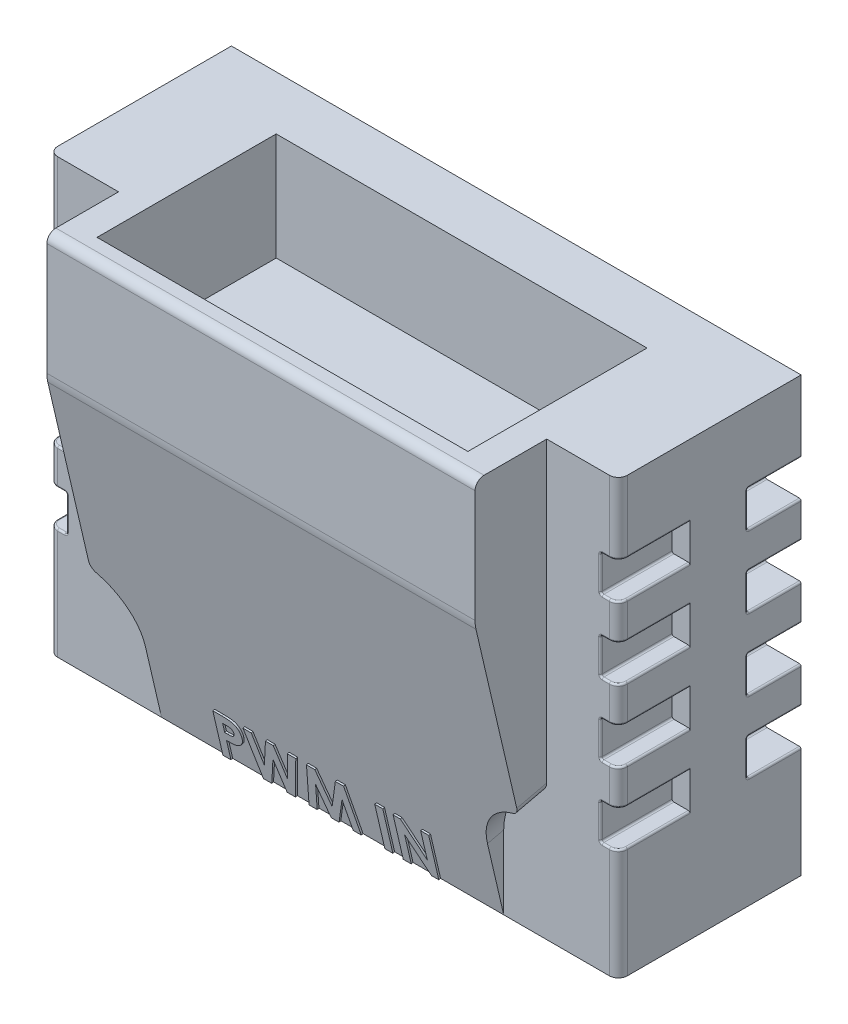
SolidWorks part; units mm, degrees
material "Polyester Resin"
ref_plane "Front Plane" through (0, 0, 0) normal (0, 0, 1) x (1, 0, 0)
ref_plane "Top Plane" through (0, 0, 0) normal (0, 1, 0) x (1, 0, 0)
ref_plane "Right Plane" through (0, 0, 0) normal (1, 0, 0) x (0, 0, -1)
sketch "Sketch1" plane through (0, 0, 0) normal (0, 0, 1) x (1, 0, 0)
  line L1 (-15.9, 12.1) -> (15.9, 12.1)
  line L2 (-15.9, 12.1) -> (-15.9, -12.1)
  line L3 (-15.9, -12.1) -> (15.9, -12.1)
  line L4 (15.9, 12.1) -> (15.9, -12.1)
  point P6 (0, 12.1)
  point P7 (15.9, 0)
  dimension "D1" = 31.8
  dimension "D2" = 24.2
extrude "Boss-Extrude1" add sketch "Sketch1" along normal mid plane 10.2
sketch "Sketch3" plane through (15.9, 0, 0) normal (1, 0, 0) x (0, 0, -1)
  line L0 (-5.1, -12.1) -> (-5.7982, -9.0978)
  line L1 (-5.7982, -9.0978) -> (-9.1, 5.1)
  line L2 (-9.1, 5.1) -> (-9.1, 12.1)
  line L3 (-9.1, 12.1) -> (-5.1, 12.1)
  line L4 (-5.1, 12.1) -> (-5.1, -12.1)
  line L5 (-5.1, 12.1) -> (5.1, 12.1) construction
  dimension "D1" = 4
  dimension "D2" = 7
extrude "Boss-Extrude2" add sketch "Sketch3" against normal blind 23.9 from offset 4 offset against normal yes
fillet "Fillet1" radius 2 1 edges at (-0.05, 5.1, 9.1)
fillet "Fillet2" radius 0.5 1 edges at (-0.05, 12.1, 9.1)
sketch "Sketch4" plane through (0, -1.746, 7.5079) normal (0, -0.2265, 0.974) x (1, 0, 0)
  line L0 (11.9, 6.7992) -> (11.9, -10.6303) construction
  line L1 (-12, 6.7992) -> (-12, -10.6303) construction
  line L2 (-9.6, -6.6303) -> (-9.6, -10.6303)
  line L3 (-12, -10.6303) -> (11.9, -10.6303) construction
  line L4 (-9.6, -10.6303) -> (-12, -10.6303)
  line L5 (-12, -10.6303) -> (-12, -3.6303)
  line L6 (9.5, -6.6303) -> (9.5, -10.6303)
  line L7 (9.5, -10.6303) -> (11.9, -10.6303)
  line L8 (11.9, -10.6303) -> (11.9, -3.6303)
  arc A0 (11.9, -3.6303) -> (9.5, -6.6303) centre (12.575, -6.6303) ccw
  arc A1 (-12, -3.6303) -> (-9.6, -6.6303) centre (-12.675, -6.6303) cw
  dimension "D1" = 2.4
  dimension "D2" = 3
  dimension "D3" = 7
extrude "Cut-Extrude1" cut sketch "Sketch4" against normal up to surface up to face at (-13.95, 0, 5.1)
fillet "Fillet4" radius 0.5 2 edges at (11.9, -5.0976, 5.8928) (-12, -5.0976, 5.8928)
sketch "Sketch5" plane through (0, 0, 5.1) normal (0, 0, 1) x (1, 0, 0)
  line L0 (15.9, -12.1) -> (15.9, 12.1) construction
  line L1 (9.5, -12.1) -> (15.9, -12.1) construction
  line L2 (0, 0) -> (0, 13.9724) construction
  line L3 (15.9, 12.1) -> (11.9, 12.1) construction
  line L4 (15.9, 8.1) -> (14.9, 8.1)
  line L5 (15.9, 8.1) -> (15.9, 6.1)
  line L6 (15.9, 6.1) -> (14.9, 6.1)
  line L7 (14.9, 8.1) -> (14.9, 6.1)
  line L8 (15.9, 4.1) -> (14.9, 4.1)
  line L9 (15.9, 4.1) -> (15.9, 2.1)
  line L10 (15.9, 2.1) -> (14.9, 2.1)
  line L11 (14.9, 4.1) -> (14.9, 2.1)
  line L12 (-15.9, -5.9) -> (-14.9, -5.9)
  line L13 (15.9, 0.1) -> (14.9, 0.1)
  line L14 (15.9, 0.1) -> (15.9, -1.9)
  line L15 (15.9, -1.9) -> (14.9, -1.9)
  line L16 (14.9, 0.1) -> (14.9, -1.9)
  line L17 (15.9, -3.9) -> (14.9, -3.9)
  line L18 (15.9, -3.9) -> (15.9, -5.9)
  line L19 (15.9, -5.9) -> (14.9, -5.9)
  line L20 (14.9, -3.9) -> (14.9, -5.9)
  line L21 (-14.9, -3.9) -> (-14.9, -5.9)
  line L22 (-15.9, -3.9) -> (-14.9, -3.9)
  line L23 (-15.9, -3.9) -> (-15.9, -5.9)
  line L24 (-15.9, -1.9) -> (-14.9, -1.9)
  line L25 (-14.9, 0.1) -> (-14.9, -1.9)
  line L26 (-15.9, 0.1) -> (-14.9, 0.1)
  line L27 (-15.9, 0.1) -> (-15.9, -1.9)
  line L28 (-15.9, 4.1) -> (-15.9, 2.1)
  line L29 (-15.9, 8.1) -> (-15.9, 6.1)
  line L30 (-15.9, 2.1) -> (-14.9, 2.1)
  line L31 (-14.9, 4.1) -> (-14.9, 2.1)
  line L32 (-15.9, 4.1) -> (-14.9, 4.1)
  line L33 (-15.9, 6.1) -> (-14.9, 6.1)
  line L34 (-14.9, 8.1) -> (-14.9, 6.1)
  line L35 (-15.9, 8.1) -> (-14.9, 8.1)
  circle A0 centre (13.4, -9.6) radius 1.6
  circle A1 centre (-13.4, -9.6) radius 1.6
  dimension "D1" = 2.5
  dimension "D2" = 3.2
  dimension "D3" = 2.5
  dimension "D4" = 4
  dimension "D5" = 2
  dimension "D6" = 2
  dimension "D7" = 1
  dimension "D8" = 2
  dimension "D9" = 2
extrude "Cut-Extrude2" cut sketch "Sketch5" against normal blind 4 contours L26 L27 L24 L25 | L22 L23 L12 L21 | L29 L33 L34 L35 | L5 L6 L7 L4 | L9 L10 L11 L8 | L14 L15 L16 L13 | L18 L19 L20 L17 | L31 L30 L28 L32
fillet "Fillet5" radius 0.5 10 edges at (-15.9, -9, 5.1) (-15.9, -2.9, 5.1) (-15.9, 1.1, 5.1) (-15.9, 5.1, 5.1) (-15.9, 10.1, 5.1) (15.9, -9, 5.1) (15.9, -2.9, 5.1) (15.9, 1.1, 5.1) (15.9, 5.1, 5.1) (15.9, 10.1, 5.1)
fillet "Fillet6" radius 0.1 36 edges at (15.9, 6.1, 2.85) (15.9, 8.1, 2.85) (15.9, 4.1, 2.85) (15.9, 2.1, 2.85) (15.9, -1.9, 2.85) (15.9, 0.1, 2.85) (15.9, -3.9, 2.85) (15.9, -5.9, 2.85) (15.7536, 6.1, 4.9536) (15.7536, 8.1, 4.9536) (15.7536, 4.1, 4.9536) (15.7536, 2.1, 4.9536) (15.7536, -1.9, 4.9536) (15.7536, 0.1, 4.9536) (15.7536, -3.9, 4.9536) (15.7536, -5.9, 4.9536) (15.15, 6.1, 5.1) (15.15, 8.1, 5.1) (15.15, 4.1, 5.1) (15.15, 2.1, 5.1) (15.15, -1.9, 5.1) (15.15, 0.1, 5.1) (15.15, -3.9, 5.1) (15.15, -5.9, 5.1) (14.9, 6.1, 3.1) (14.9, 8.1, 3.1) (14.9, 7.1, 5.1) (14.9, 4.1, 3.1) (14.9, 2.1, 3.1) (14.9, 3.1, 5.1) (14.9, -1.9, 3.1) (14.9, 0.1, 3.1) (14.9, -0.9, 5.1) (14.9, -3.9, 3.1) (14.9, -4.9, 5.1) (14.9, -5.9, 3.1)
fillet "Fillet7" radius 0.1 36 edges at (-15.9, 0.1, 2.85) (-15.9, 4.1, 2.85) (-15.9, -3.9, 2.85) (-15.9, -5.9, 2.85) (-15.9, -1.9, 2.85) (-15.9, 2.1, 2.85) (-15.9, 6.1, 2.85) (-15.9, 8.1, 2.85) (-15.7536, 0.1, 4.9536) (-15.7536, 4.1, 4.9536) (-15.7536, -3.9, 4.9536) (-15.7536, -5.9, 4.9536) (-15.7536, -1.9, 4.9536) (-15.7536, 2.1, 4.9536) (-15.7536, 6.1, 4.9536) (-15.7536, 8.1, 4.9536) (-15.15, 0.1, 5.1) (-15.15, 4.1, 5.1) (-15.15, -3.9, 5.1) (-15.15, -5.9, 5.1) (-15.15, -1.9, 5.1) (-15.15, 2.1, 5.1) (-15.15, 6.1, 5.1) (-15.15, 8.1, 5.1) (-14.9, 0.1, 3.1) (-14.9, 4.1, 3.1) (-14.9, -3.9, 3.1) (-14.9, -5.9, 3.1) (-14.9, -4.9, 5.1) (-14.9, -0.9, 5.1) (-14.9, -1.9, 3.1) (-14.9, 2.1, 3.1) (-14.9, 3.1, 5.1) (-14.9, 6.1, 3.1) (-14.9, 7.1, 5.1) (-14.9, 8.1, 3.1)
sketch "Sketch6" plane through (0, 12.1, 0) normal (0, 1, 0) x (1, 0, 0)
  line L0 (11.9, -9.1) -> (-12, -9.1) construction
  line L1 (10.3, -7.9) -> (-10.4, -7.9)
  line L2 (10.3, -7.9) -> (10.3, 2.1)
  line L3 (10.3, 2.1) -> (-10.4, 2.1)
  line L4 (-10.4, -7.9) -> (-10.4, 2.1)
  line L5 (-12, -5.1) -> (-12, -8.6) construction
  line L6 (15.9, 5.1) -> (-15.9, 5.1) construction
  line L7 (11.9, -5.1) -> (11.9, -8.6) construction
  dimension "D1" = 1.2
  dimension "D2" = 1.6
  dimension "D3" = 3
  dimension "D4" = 1.6
extrude "Cut-Extrude3" cut sketch "Sketch6" against normal blind 6
sketch "Sketch7" plane through (0, 0, -5.1) normal (0, 0, -1) x (-1, 0, 0)
  line L0 (-15.9, -12.1) -> (-15.9, 12.1) construction
  line L1 (-15.9, 8.1) -> (-13.9, 8.1)
  line L2 (-15.9, 8.1) -> (-15.9, 6.1)
  line L3 (-15.9, 6.1) -> (-13.9, 6.1)
  line L4 (-13.9, 8.1) -> (-13.9, 6.1)
  line L5 (-15.9, 12.1) -> (15.9, 12.1) construction
  line L6 (-15.9, 4.1) -> (-13.9, 4.1)
  line L7 (-15.9, 4.1) -> (-15.9, 2.1)
  line L8 (-15.9, 2.1) -> (-13.9, 2.1)
  line L9 (-13.9, 4.1) -> (-13.9, 2.1)
  line L10 (-15.9, 0.1) -> (-13.9, 0.1)
  line L11 (-15.9, 0.1) -> (-15.9, -1.9)
  line L12 (-15.9, -1.9) -> (-13.9, -1.9)
  line L13 (-13.9, 0.1) -> (-13.9, -1.9)
  line L14 (-15.9, -3.9) -> (-13.9, -3.9)
  line L15 (-15.9, -3.9) -> (-15.9, -5.9)
  line L16 (-15.9, -5.9) -> (-13.9, -5.9)
  line L17 (-13.9, -3.9) -> (-13.9, -5.9)
  line L18 (0, 0) -> (0, 20.7602) construction
  line L19 (15.9, -5.9) -> (13.9, -5.9)
  line L20 (13.9, -3.9) -> (13.9, -5.9)
  line L21 (15.9, -3.9) -> (13.9, -3.9)
  line L22 (15.9, -3.9) -> (15.9, -5.9)
  line L23 (15.9, -1.9) -> (13.9, -1.9)
  line L24 (13.9, 0.1) -> (13.9, -1.9)
  line L25 (15.9, 0.1) -> (13.9, 0.1)
  line L26 (15.9, 0.1) -> (15.9, -1.9)
  line L27 (15.9, 2.1) -> (13.9, 2.1)
  line L28 (13.9, 4.1) -> (13.9, 2.1)
  line L29 (15.9, 4.1) -> (13.9, 4.1)
  line L30 (15.9, 4.1) -> (15.9, 2.1)
  line L31 (15.9, 6.1) -> (13.9, 6.1)
  line L32 (13.9, 8.1) -> (13.9, 6.1)
  line L33 (15.9, 8.1) -> (13.9, 8.1)
  line L34 (15.9, 8.1) -> (15.9, 6.1)
  dimension "D1" = 4
  dimension "D2" = 2
  dimension "D3" = 2
  dimension "D4" = 2
  dimension "D5" = 2
  dimension "D6" = 2
extrude "Cut-Extrude4" cut sketch "Sketch7" against normal blind 3
fillet "Fillet8" radius 0.1 56 edges at (-15.9, 8.1, -3.6) (-15.9, 4.1, -3.6) (-15.9, 0.1, -3.6) (-15.9, -3.9, -3.6) (-15.9, -5.9, -3.6) (-15.9, -1.9, -3.6) (-15.9, 2.1, -3.6) (15.9, 7.1, -2.1) (15.9, 0.1, -3.6) (-13.9, 8.1, -3.6) (-14.9, 8.1, -2.1) (-13.9, 4.1, -3.6) (-14.9, 4.1, -2.1) (-13.9, 0.1, -3.6) (-14.9, 0.1, -2.1) (-14.9, -3.9, -2.1) (-13.9, -3.9, -3.6) (-13.9, -5.9, -3.6) (-13.9, -1.9, -3.6) (-13.9, 2.1, -3.6) (-14.9, -5.9, -2.1) (-14.9, -1.9, -2.1) (-14.9, 2.1, -2.1) (-14.9, 6.1, -2.1) (-15.9, 6.1, -3.6) (-13.9, 6.1, -3.6) (-15.9, 7.1, -2.1) (-15.9, 3.1, -2.1) (-15.9, -0.9, -2.1) (-15.9, -4.9, -2.1) (14.9, 4.1, -2.1) (14.9, 6.1, -2.1) (15.9, 6.1, -3.6) (13.9, 6.1, -3.6) (14.9, 8.1, -2.1) (15.9, 8.1, -3.6) (13.9, 8.1, -3.6) (15.9, 4.1, -3.6) (13.9, 4.1, -3.6) (13.9, 2.1, -3.6) (15.9, 2.1, -3.6) (15.9, 3.1, -2.1) (14.9, 2.1, -2.1) (14.9, -1.9, -2.1) (13.9, 0.1, -3.6) (14.9, -5.9, -2.1) (15.9, -0.9, -2.1) (14.9, 0.1, -2.1) (15.9, -1.9, -3.6) (13.9, -1.9, -3.6) (15.9, -5.9, -3.6) (13.9, -5.9, -3.6) (15.9, -3.9, -3.6) (14.9, -3.9, -2.1) (15.9, -4.9, -2.1) (13.9, -3.9, -3.6)
sketch "Sketch9" plane through (0, -12.1, 0) normal (0, -1, 0) x (1, 0, 0)
  line L0 (-9.6, 5.1) -> (9.5, 5.1) construction
  line L1 (-8.3, 3.8) -> (8.3, 3.8)
  line L2 (-8.3, 3.8) -> (-8.3, -0.6)
  line L3 (-8.3, -0.6) -> (8.3, -0.6)
  line L4 (8.3, 3.8) -> (8.3, -0.6)
  line L5 (-15.9, -5.1) -> (15.9, -5.1) construction
  line L6 (-15.9, 4.6) -> (-15.9, -5.1) construction
  dimension "D1" = 1.3
  dimension "D2" = 7.6
  dimension "D3" = 7.6
  dimension "D4" = 4.5
extrude "Cut-Extrude5" cut sketch "Sketch9" against normal blind 3
sketch "Sketch10" plane through (0, -1.746, 7.5079) normal (0, -0.2265, 0.974) x (1, 0, 0)
  line L0 (-9.6, -10.6303) -> (9.5, -10.6303) construction
  text T0 "PWM IN" font "Century Gothic" height 2.5
extrude "Boss-Extrude3" add sketch "Sketch10" along normal blind 0.1
